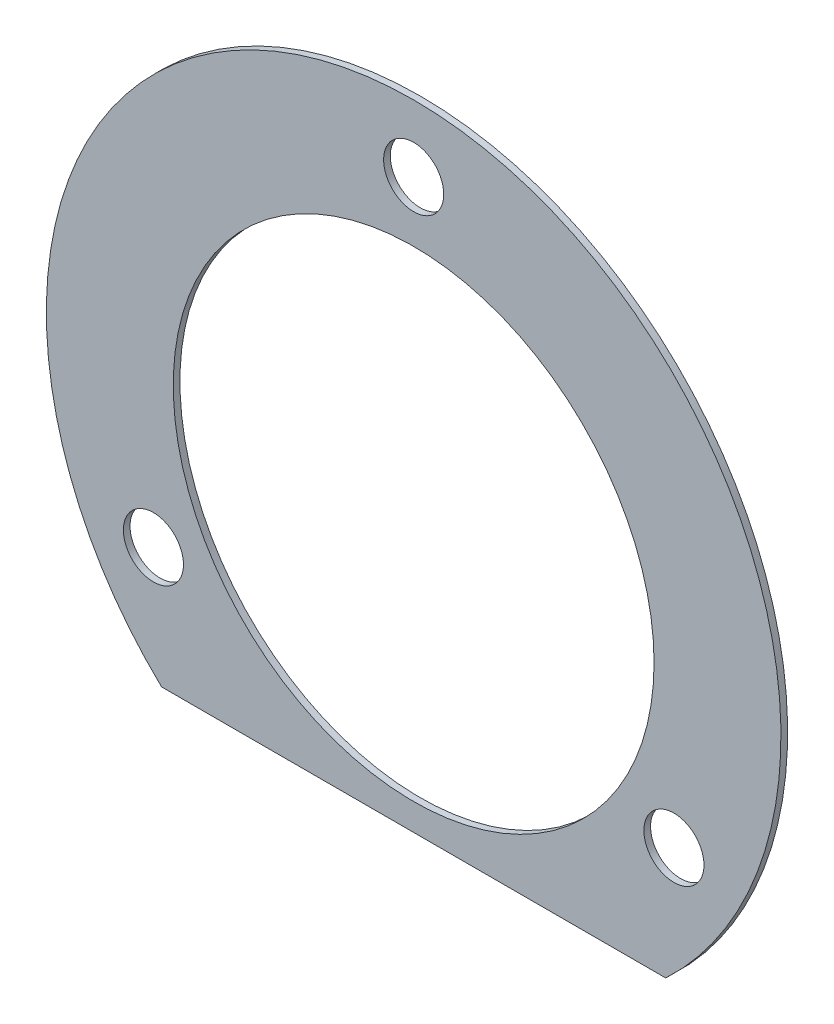
SolidWorks part; units mm, degrees
ref_plane "Piano frontale" through (0, 0, 0) normal (0, 0, 1) x (1, 0, 0)
ref_plane "Piano superiore" through (0, 0, 0) normal (0, 1, 0) x (1, 0, 0)
ref_plane "Piano destro" through (0, 0, 0) normal (1, 0, 0) x (0, 0, -1)
sketch "Schizzo1" plane through (0, 0, 0) normal (0, 0, 1) x (1, 0, 0)
  circle A0 centre (0, 0) radius 36
  circle A1 centre (0, 0) radius 55
  dimension "D1" = 72
  dimension "D2" = 110
extrude "Estrusione-Estrusione1" add sketch "Schizzo1" along normal blind 1
sketch "Schizzo2" plane through (0, 0, 1) normal (0, 0, 1) x (1, 0, 0)
  line L0 (0, 52.7907) -> (0, 0) construction
  line L1 (0, 0) -> (-38.9711, -22.5) construction
  line L2 (0, 0) -> (38.9711, -22.5) construction
  circle A1 centre (0, 45) radius 4.5
  circle A2 centre (38.9711, -22.5) radius 4.5
  circle A3 centre (-38.9711, -22.5) radius 4.5
  point P12 (0, 0)
  dimension "D1" = 45
  dimension "D2" = 9
  dimension "D4" = 120
  dimension "D5" = 120
  dimension "D3" = 3
extrude "Taglio-Estrusione1" cut sketch "Schizzo2" against normal through all
sketch "Schizzo4" plane through (0, 0, 0) normal (0, 0, 1) x (1, 0, 0)
  line L0 (37.7492, -40) -> (-37.7492, -40)
  line L1 (-16.5349, 0) -> (23.7641, 0) construction
  arc A0 (37.7492, -40) -> (-37.7492, -40) centre (0, 0) ccw
  dimension "D1" = 55
  dimension "D2" = 40
extrude "Taglio-Estrusione2" cut sketch "Schizzo4" along normal through all flip side to cut
